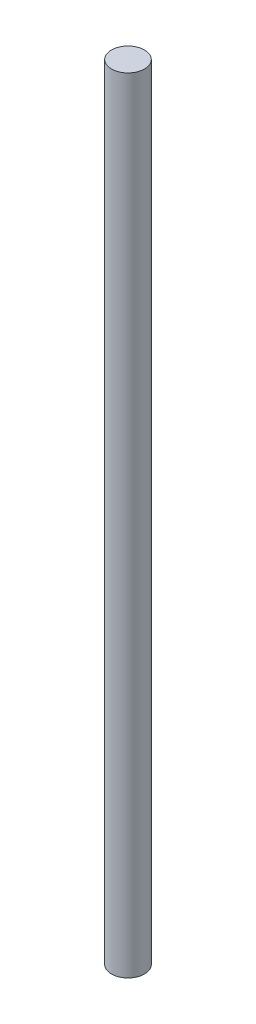
SolidWorks part; units mm, degrees
material "Plain Carbon Steel"
ref_plane "Front Plane" through (0, 0, 0) normal (0, 0, 1) x (1, 0, 0)
ref_plane "Top Plane" through (0, 0, 0) normal (0, 1, 0) x (1, 0, 0)
ref_plane "Right Plane" through (0, 0, 0) normal (1, 0, 0) x (0, 0, -1)
sketch "Sketch1" plane through (0, 0, 0) normal (0, 1, 0) x (1, 0, 0)
  circle A0 centre (0, 0) radius 4
  dimension "D1" = 8
extrude "Boss-Extrude1" add sketch "Sketch1" against normal blind 190
